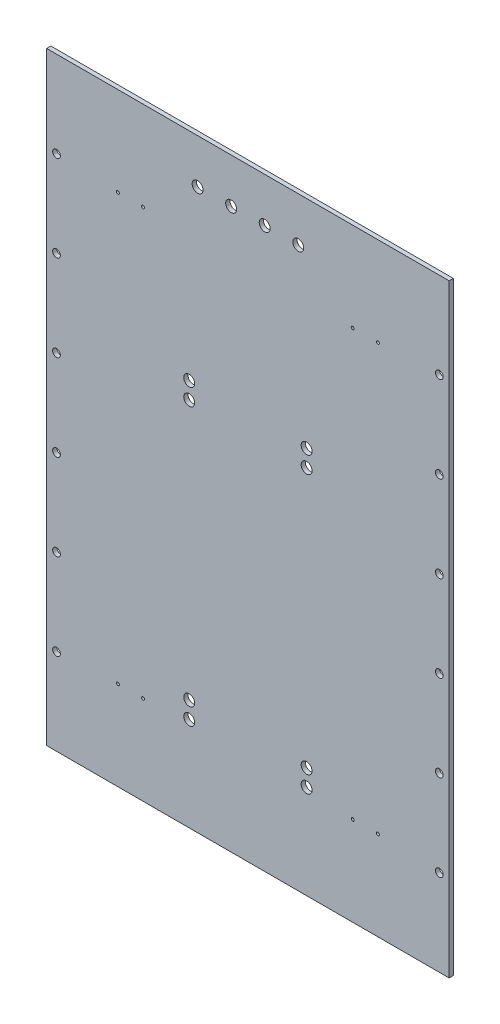
SolidWorks part; units mm, degrees
material "Plain Carbon Steel"
ref_plane "Front Plane" through (0, 0, 0) normal (0, 0, 1) x (1, 0, 0)
ref_plane "Top Plane" through (0, 0, 0) normal (0, 1, 0) x (1, 0, 0)
ref_plane "Right Plane" through (0, 0, 0) normal (1, 0, 0) x (0, 0, -1)
sketch "Sketch1" plane through (0, 0, 0) normal (0, 0, 1) x (1, 0, 0)
  line L1 (-304.8, -457.2) -> (304.8, -457.2)
  line L2 (-304.8, -457.2) -> (-304.8, 457.2)
  line L3 (-304.8, 457.2) -> (304.8, 457.2)
  line L4 (304.8, -457.2) -> (304.8, 457.2)
  line L5 (-304.8, -457.2) -> (304.8, 457.2) construction
  line L6 (-304.8, 457.2) -> (304.8, -457.2) construction
  point P0 (0, 0)
  dimension "D1" = 914.4
  dimension "D2" = 609.6
extrude "Boss-Extrude1" add sketch "Sketch1" along normal mid plane 6.35
sketch "Sketch2" plane through (0, 0, 3.175) normal (0, 0, 1) x (1, 0, 0)
  line L0 (-304.8, -457.2) -> (304.8, -457.2) construction
  line L1 (-304.8, 457.2) -> (-304.8, -457.2) construction
  line L2 (0, 457.2) -> (0, -457.2) construction
  line L3 (304.8, 457.2) -> (-304.8, 457.2) construction
  line L4 (304.8, 0) -> (-304.8, 0) construction
  line L5 (304.8, -457.2) -> (304.8, 457.2) construction
  point P0 (-196.85, -322.2625)
  point P1 (-158.75, -322.2625)
  point P14 (196.85, -322.2625)
  point P15 (158.75, -322.2625)
  point P16 (158.75, 322.2625)
  point P17 (196.85, 322.2625)
  point P18 (-158.75, 322.2625)
  point P19 (-196.85, 322.2625)
  dimension "D1" = 134.9375
  dimension "D2" = 107.95
  dimension "D3" = 38.1
hole_wizard "#8 Clearance Hole1" positions "Sketch2" profile "Sketch3" hole size "#8" standard "ANSI Inch" end condition up to next
sketch "Sketch3" plane through (-196.85, -322.2625, 3.175) normal (1, 0, 0) x (0, -1, 0)
  line L0 (0, 0) -> (0, 6.35)
  line L1 (0, 6.35) -> (2.2479, 6.35)
  line L2 (2.2479, 6.35) -> (2.2479, 0)
  line L5 (2.2479, 0) -> (0, 0)
  line L11 (0, -6.35) -> (0, 107.95) construction
  dimension "Thru Hole Dia." = 4.4958
  dimension "Thru Hole Depth" = 6.35
sketch "Sketch4" plane through (0, 0, 3.175) normal (0, 0, 1) x (1, 0, 0)
  line L0 (0, 457.2) -> (0, -457.2) construction
  line L1 (304.8, 457.2) -> (-304.8, 457.2) construction
  line L2 (-304.8, -457.2) -> (304.8, -457.2) construction
  line L3 (-88.9, 129.5426) -> (-88.9, 104.1426) construction
  circle A0 centre (76.2, 389.8926) radius 6.7462 construction
  circle A1 centre (76.2, 389.8926) radius 6.7462 construction
  circle A2 centre (-25.4, 389.8926) radius 6.7462 construction
  circle A3 centre (25.4, 389.8926) radius 6.7462 construction
  circle A4 centre (-76.2, 389.8926) radius 6.7462 construction
  circle A5 centre (-25.4, 389.8926) radius 6.7462 construction
  circle A6 centre (25.4, 389.8926) radius 6.7462 construction
  circle A7 centre (-76.2, 389.8926) radius 6.7462 construction
  circle A8 centre (76.2, 389.8926) radius 8.2702
  circle A9 centre (-25.4, 389.8926) radius 8.2702
  circle A10 centre (25.4, 389.8926) radius 8.2702
  circle A11 centre (-76.2, 389.8926) radius 8.2702
  circle A12 centre (-88.9, 129.5426) radius 8.2702
  circle A13 centre (-88.9, 104.1426) radius 8.2702
  circle A14 centre (-88.9, -289.5574) radius 8.2702
  circle A15 centre (-88.9, -314.9574) radius 8.2702
  circle A16 centre (88.9, -314.9574) radius 8.2702
  circle A17 centre (88.9, -289.5574) radius 8.2702
  circle A18 centre (88.9, 104.1426) radius 8.2702
  circle A19 centre (88.9, 129.5426) radius 8.2702
  point P34 (0, 0)
  point P37 (0, 0)
  point P38 (0, 0)
  dimension "D3" = 88.9
  dimension "D2" = 25.4
  dimension "D4" = 260.35
  dimension "D5" = 679.45
  dimension "D6" = 25.4
  dimension "D1" = 1.524
extrude "Cut-Extrude1" cut sketch "Sketch4" against normal through all both and the other way through all
sketch "Sketch8" plane through (0, 0, 3.175) normal (0, 0, 1) x (1, 0, 0)
  line L0 (-304.8, 457.2) -> (-304.8, -457.2) construction
  line L1 (-304.8, -457.2) -> (304.8, -457.2) construction
  line L2 (0, 457.2) -> (0, -457.2) construction
  line L3 (304.8, 457.2) -> (-304.8, 457.2) construction
  circle A0 centre (158.75, -322.2625) radius 2.2479 construction
  point P0 (-289.8775, -326.5714)
  point P7 (-289.8775, -195.9429)
  point P8 (-289.8775, -65.3143)
  point P9 (-289.8775, 65.3143)
  point P10 (-289.8775, 195.9429)
  point P11 (-289.8775, 326.5714)
  point P17 (289.8775, 326.5714)
  point P18 (289.8775, 195.9429)
  point P19 (289.8775, 65.3143)
  point P20 (289.8775, -65.3143)
  point P21 (289.8775, -195.9429)
  point P22 (289.8775, -326.5714)
  dimension "D1" = 14.9225
  dimension "D2" = 130.6286
  dimension "D4" = 126.3196
  dimension "D3" = 6
hole_wizard "3/8 Clearance Hole1" positions "Sketch8" profile "Sketch9" hole size "3/8" standard "ANSI Inch" end condition up to next
sketch "Sketch9" plane through (-289.8775, -326.5714, 3.175) normal (1, 0, 0) x (0, -1, 0)
  line L0 (0, 0) -> (0, 6.35)
  line L1 (0, 6.35) -> (5.842, 6.35)
  line L2 (5.842, 6.35) -> (5.842, 0)
  line L5 (5.842, 0) -> (0, 0)
  line L11 (0, -6.35) -> (0, 107.95) construction
  dimension "Thru Hole Dia." = 11.684
  dimension "Thru Hole Depth" = 6.35
